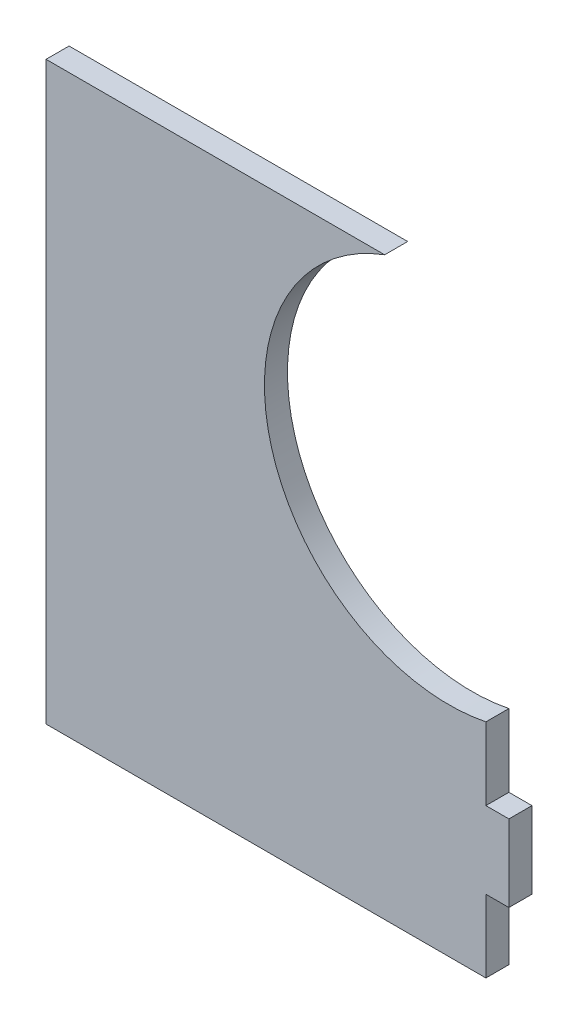
SolidWorks part; units mm, degrees
ref_plane "Alzado" through (0, 0, 0) normal (0, 0, 1) x (1, 0, 0)
ref_plane "Planta" through (0, 0, 0) normal (0, 1, 0) x (1, 0, 0)
ref_plane "Vista lateral" through (0, 0, 0) normal (1, 0, 0) x (0, 0, -1)
sketch "Croquis1" plane through (0, 0, 0) normal (0, 0, 1) x (1, 0, 0)
  line L0 (-3, 0.8384) -> (-60.3, 0.8384)
  line L2 (-31.8, 75.8384) -> (-3, 75.8384) construction
  line L3 (-60.3, 0.8384) -> (-60.3, 75.8384)
  line L4 (-60.3, 75.8384) -> (-16.1879, 75.8384)
  line L6 (-3, 0.8384) -> (-3, 10.2884) construction
  line L7 (-3, 10.2884) -> (-3, 0.8384)
  line L9 (-3, 10.2884) -> (0, 10.2884)
  line L10 (0, 0.8384) -> (0, 10.2884) construction
  line L11 (0, 10.2884) -> (0, 20.2884)
  line L12 (0, 20.2884) -> (-3, 20.2884)
  line L13 (-3, 20.2884) -> (-3, 29.7384)
  arc A1 (-3, 29.7384) -> (-16.1879, 75.8384) centre (-7.8, 53.3016) cw
  point P4 (0, 0)
  point P6 (0, 0)
  point P7 (0, 0)
  dimension "D1" = 57.3
  dimension "D2" = 28.9
  dimension "D3" = 10
  dimension "D4" = 9.45
extrude "Saliente-Extruir1" add sketch "Croquis1" along normal blind 3
